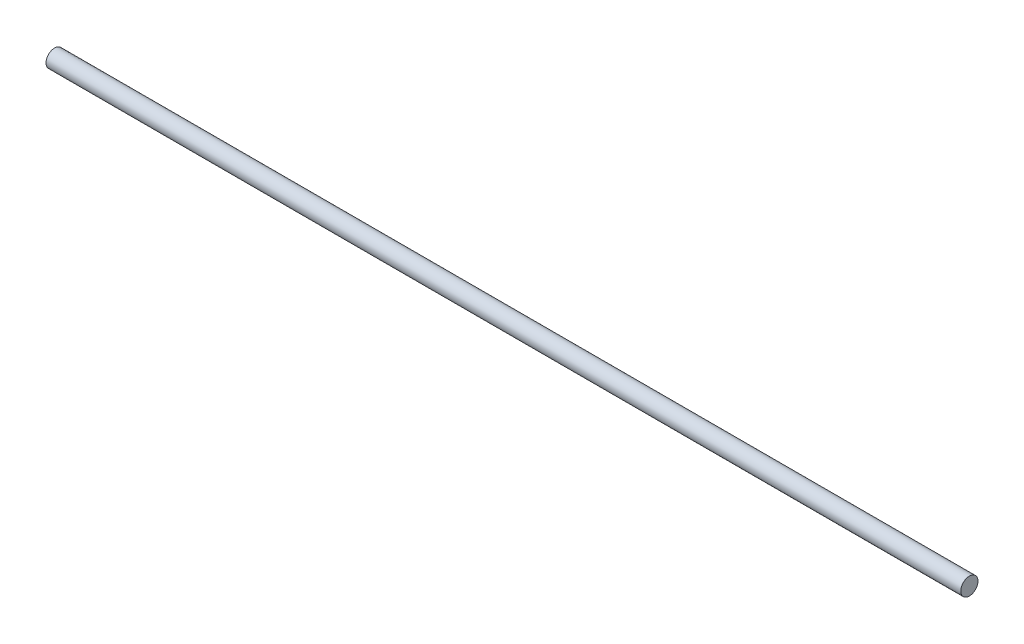
SolidWorks part; units mm, degrees
material "Plain Carbon Steel"
ref_plane "Front Plane" through (0, 0, 0) normal (0, 0, 1) x (1, 0, 0)
ref_plane "Top Plane" through (0, 0, 0) normal (0, 1, 0) x (1, 0, 0)
ref_plane "Right Plane" through (0, 0, 0) normal (1, 0, 0) x (0, 0, -1)
sketch "Sketch1" plane through (0, 0, 0) normal (1, 0, 0) x (0, 0, -1)
  circle A0 centre (0, 0) radius 2.5
  dimension "D1" = 5
extrude "Boss-Extrude1" add sketch "Sketch1" along normal blind 265
